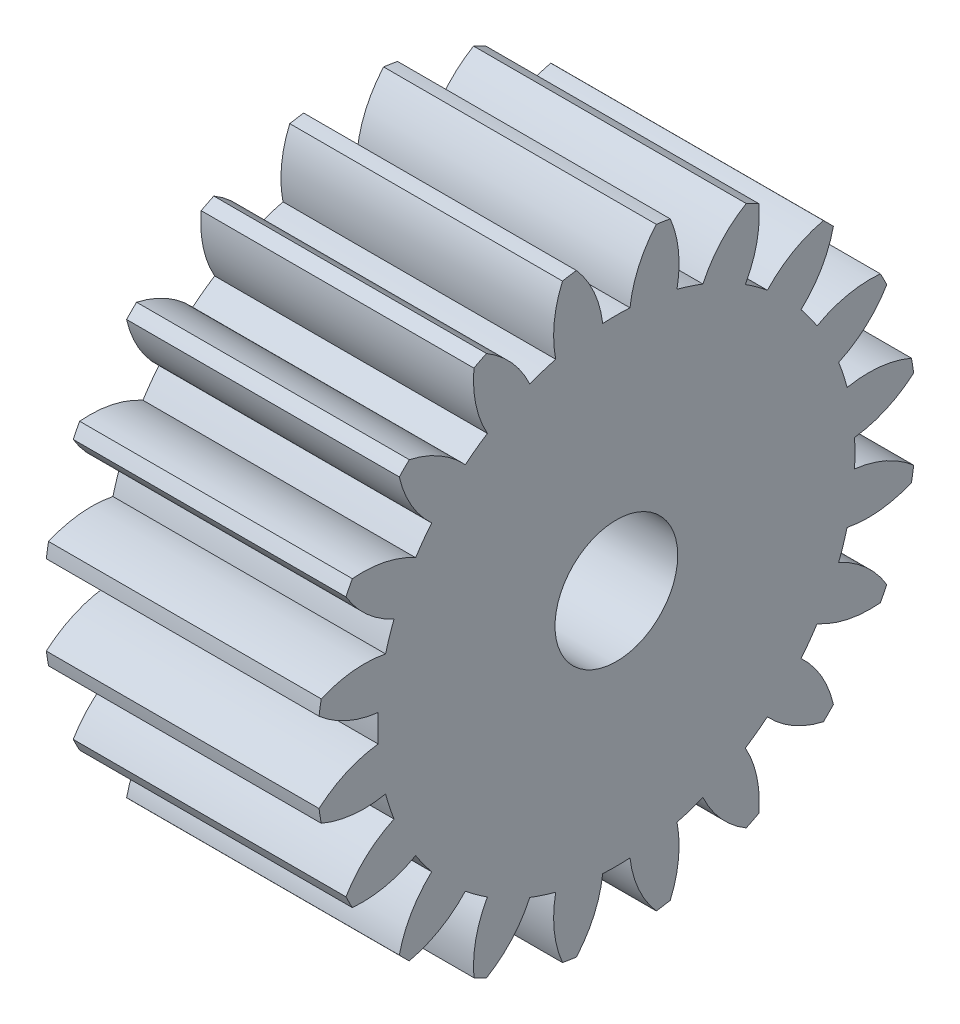
SolidWorks part; units mm, degrees
ref_plane "Plane1" through (0, 0, 0) normal (0, 0, 1) x (1, 0, 0)
ref_plane "Plane2" through (0, 0, 0) normal (0, 1, 0) x (1, 0, 0)
ref_plane "Plane3" through (0, 0, 0) normal (1, 0, 0) x (0, 0, -1)
other "Configuration Table"
sketch "HoldingSke" plane through (0, 0, 0) normal (0, 1, 0) x (1, 0, 0)
  line L0 (0, 0) -> (0.9397, -0.342)
  line L1 (-15, 0) -> (100, 0) construction
  line L2 (0, 0) -> (-2.1039, 2.3779)
  line L3 (0, 0) -> (-11.863, 4.5341)
  line L4 (0, 0) -> (8.1152, 2.9537)
  line L5 (0, 0) -> (-46.8476, -17.4728)
  line L6 (0, 0) -> (-8.2896, -5.593)
  line L7 (-2.1039, 2.3779) -> (8.6586, 51.2059)
  line L8 (-76.2, 54.61) -> (-75.5, 54.61)
  line L9 (-71.009, 38.7566) -> (-53.1078, 45.2721)
  line L10 (-76.2, 71.12) -> (104.1128, 71.12)
  line L11 (0, 0) -> (-10, 0)
  line L12 (-76.2, 101.6) -> (-76.162, 101.6)
  line L13 (24.9733, 27.94) -> (52.9518, 28.4284)
  line L14 (24.9733, 27.94) -> (24.9743, 27.94)
  line L15 (24.9733, 27.94) -> (100.4006, 29.5858)
  line L16 (-63.627, -1) -> (-12.827, -1)
  circle A0 centre (0, 0) radius 2
  circle A1 centre (0, 0) radius 8.749
  circle A2 centre (0, 0) radius 37.5
  circle A3 centre (0, 0) radius 2
  dimension "MHD" = 17.498
  dimension "Hub_dia" = 75
  dimension "Bore" = 4
  dimension "MBD" = 4
  dimension "Num_teeth" = 20
  dimension "Pitch" = 1
  dimension "Overall_len" = 50
  dimension "Show_teeth" = 20
  dimension "Thickness" = 10
  dimension "OAL" = 50.0001
  dimension "T_dim" = 0.7
  dimension "Ap" = 20
  dimension "H" = 19.05
  dimension "Pitch_radius" = 180.3128
  dimension "Width" = 10
  dimension "Backlash" = 0.038
  dimension "Addendum_fac" = 1
  dimension "Dedendum_fac" = 1.25
  dimension "Clearance_fac" = 0.25
  dimension "Dedendum_add" = 0.001
  dimension "Module" = 1
sketch "BasProSke" plane through (0, 0, 0) normal (0, 1, 0) x (1, 0, 0)
  line L0 (-10, 0) -> (60, 0) construction
  line L1 (0, 0) -> (0, 11)
  line L2 (0, 0) -> (10, 0)
  line L3 (10, 0) -> (10, 11)
  line L4 (10, 11) -> (0, 11)
  dimension "Thickness" = 10
  dimension "Diameter" = 22
revolve "Base-Revolve" add sketch "BasProSke" angle 360 about L0
sketch "TooCutSke" plane through (0, 0, 0) normal (1, 0, 0) x (0, 0, -1)
  line L1 (0, 0) -> (0, 107) construction
  line L2 (0, 0) -> (-0.8511, 9.9637) construction
  line L3 (0, 0) -> (-3.1206, 19.7028) construction
  line L4 (-0.8511, 9.9637) -> (-1.5603, 9.8514) construction
  arc A0 (0.4999, 8.7347) -> (-0.4999, 8.7347) centre (0, 0) ccw
  arc A1 (1.4852, 10.9249) -> (-1.4852, 10.9249) centre (0, 0) ccw
  circle A2 centre (0, 0) radius 10 construction
  circle A3 centre (0, 0) radius 9.3969 construction
  arc A4 (-0.4999, 8.7347) -> (-1.4852, 10.9249) centre (-4.4722, 8.2645) ccw
  arc A5 (1.4852, 10.9249) -> (0.4999, 8.7347) centre (4.4722, 8.2645) ccw
  dimension "Root_dia" = 17.498
  dimension "Overcut_dia" = 22.0508
  dimension "Pitch_dia" = 20
  dimension "Base_dia" = 18.7939
  dimension "Flank_rad" = 4
  dimension "Half_ang" = 9
  dimension "Half_CT" = 0.7181
extrude "ToothCut" cut sketch "TooCutSke" along normal through all
fillet "Breaks" [suppressed] radius 0.02
fillet "RootFillets" [suppressed] radius 0.251
pattern_circular "TeethCuts" count 20 every 18 about axis through (-10, 0, 0) along (1, 0, 0) of "ToothCut", "RootFillets", "Breaks"
sketch "HubNeaOneSke" plane through (0, 0, 0) normal (-1, 0, 0) x (0, 0, 1)
  circle A0 centre (0, 0) radius 8.749
  dimension "Diameter" = 17.498
extrude "HubNearOne" [suppressed] add sketch "HubNeaOneSke" along normal blind 40.0001
sketch "HubNeaBotSke" plane through (0, 0, 0) normal (-1, 0, 0) x (0, 0, 1)
  circle A0 centre (0, 0) radius 8.749
  dimension "Diameter" = 17.498
extrude "HubNearBoth" [suppressed] add sketch "HubNeaBotSke" along normal blind 20
ref_plane "FarPln" through (10, 0, 0) normal (1, 0, 0) x (0, 0, -1)
sketch "HubFarSke" plane through (10, 0, 0) normal (1, 0, 0) x (0, 0, -1)
  circle A0 centre (0, 0) radius 8.749
  dimension "Diameter" = 17.498
extrude "HubFar" [suppressed] add sketch "HubFarSke" along normal blind 20
sketch "BorSke" plane through (0, 0, 0) normal (1, 0, 0) x (0, 0, -1)
  circle A0 centre (0, 0) radius 2
  dimension "Diameter" = 4
extrude "Bore" cut sketch "BorSke" along normal mid plane 100.0001
sketch "KeySke" plane through (0, 0, 0) normal (1, 0, 0) x (0, 0, -1)
  line L0 (-0.8, 0) -> (-0.8, 2.7)
  line L1 (-0.8, 2.7) -> (0.8, 2.7)
  line L2 (0.8, 2.7) -> (0.8, 0)
  line L3 (0, 0) -> (0, 34) construction
  line L4 (-0.8, 0) -> (0.8, 0)
  dimension "Offset" = 2.7
  dimension "Width" = 1.6
extrude "Keyway" [suppressed] cut sketch "KeySke" along normal mid plane 100.0001
pattern_circular "Keyway2" [suppressed] count 2 every 90 about axis through (-10, 0, 0) along (1, 0, 0)
sketch "Sketch1" plane through (10, 0, 0) normal (1, 0, 0) x (0, 0, -1)
  circle A0 centre (0, 0) radius 2.25
extrude "Cut-Extrude1" cut sketch "Sketch1" against normal through all
equation "' \"Module@HoldingSke\" = 6.35"
equation "' \"Num_teeth@HoldingSke\" = 12"
equation "' \"Ap@HoldingSke\" =  20"
equation "' \"Ap@HoldingSke\" = 20"
equation "' \"Width@HoldingSke\" = 0.5 * 25.4"
equation "' \"Hub_dia@HoldingSke\"= 1 * 25.4"
equation "' \"Hub_dia@HoldingSke\" = 1 * 25.4"
equation "' \"Overall_len@HoldingSke\" = 1.0 * 25.4"
equation "' \"Bore@HoldingSke\" = 0.75 * 25.4"
equation "' \"T_dim@HoldingSke\" = 0.1 * 25.4"
equation "' \"Width@KeySke\" = 0.25 * 25.4"
equation "' \"Show_teeth@HoldingSke\" = 13"
equation "' \"Backlash@HoldingSke\" = 0.009 * 25.4"
equation "' \"Addendum_fac@HoldingSke\" = 1.0"
equation "' \"Dedendum_fac@HoldingSke\" = 1.25"
equation "' \"Dedendum_add@HoldingSke\" = 0.00005 * 25.4"
equation "' \"Clearance_fac@HoldingSke\" = 0.25"
equation "\"Pitch@HoldingSke\" = 1 / \"Module@HoldingSke\""
equation "\"Overcut_dia@TooCutSke\" = (\"Num_teeth@HoldingSke\" + 2 * \"Addendum_fac@HoldingSke\") / \"Pitch@HoldingSke\" + 0.002 * 25.4"
equation "\"Pitch_dia@TooCutSke\" = \"Num_teeth@HoldingSke\" / \"Pitch@HoldingSke\""
equation "\"Base_dia@TooCutSke\" = \"Num_teeth@HoldingSke\" / \"Pitch@HoldingSke\" * cos((\"Ap@HoldingSke\"  * 3.14159265 / 180))"
equation "\"Root_dia@TooCutSke\" = (\"Num_teeth@HoldingSke\" + 2) / \"Pitch@HoldingSke\" - 2 * (\"Addendum_fac@HoldingSke\" + \"Dedendum_fac@HoldingSke\") / \"Pitch@HoldingSke\" - \"Dedendum_add@HoldingSke\" * 2"
equation "\"Half_ang@TooCutSke\" = 180 / \"Num_teeth@HoldingSke\""
equation "\"Half_CT@TooCutSke\" = \"Num_teeth@HoldingSke\" / \"Pitch@HoldingSke\" * sin((3.14159265 / 2 / \"Num_teeth@HoldingSke\")) / 2 - 7 * \"Backlash@HoldingSke\" / 4"
equation "\"Flank_rad@TooCutSke\" = \"Num_teeth@HoldingSke\" / \"Pitch@HoldingSke\" / 5"
equation "\"Radius@RootFillets\" = \"Clearance_fac@HoldingSke\" / \"Pitch@HoldingSke\" + \"Dedendum_add@HoldingSke\""
equation "\"Break_rad@Breaks\" = 0.02 / \"Pitch@HoldingSke\""
equation "\"Thickness@HoldingSke\" = \"Width@HoldingSke\""
equation "\"OAL@HoldingSke\" = \"Thickness@HoldingSke\""
equation "\"MHD@HoldingSke\" = (\"Num_teeth@HoldingSke\" + 2) / \"Pitch@HoldingSke\" - 2 * (\"Addendum_fac@HoldingSke\" + \"Dedendum_fac@HoldingSke\")  / \"Pitch@HoldingSke\" - \"Dedendum_add@HoldingSke\" * 2"
equation "\"MBD@HoldingSke\" = (\"Num_teeth@HoldingSke\" + 2) / \"Pitch@HoldingSke\" - 2 * (\"Addendum_fac@HoldingSke\" + \"Dedendum_fac@HoldingSke\")  / \"Pitch@HoldingSke\" - \"Dedendum_add@HoldingSke\" * 2 - 0.002 * 25.4"
equation "\"MHD@HoldingSke\" = ((sgn( \"MHD@HoldingSke\" - \"Hub_dia@HoldingSke\" )-1)*( \"MHD@HoldingSke\" - \"Hub_dia@HoldingSke\" ))/-2+ \"Hub_dia@HoldingSke\""
equation "\"MBD@HoldingSke\" = ((sgn( \"MBD@HoldingSke\" - \"Bore@HoldingSke\" )-1)*( \"MBD@HoldingSke\" - \"Bore@HoldingSke\" ))/-2+ \"Bore@HoldingSke\""
equation "\"OAL@HoldingSke\" = ((sgn( \"OAL@HoldingSke\" - \"Overall_len@HoldingSke\" )+1)*( \"OAL@HoldingSke\" - \"Overall_len@HoldingSke\" ))/2 + \"Overall_len@HoldingSke\" + 0.000002 * 25.4"
equation "\"Num_teeth@TeethCuts\" = int( \"Show_teeth@HoldingSke\" ) + 1"
equation "\"Num_teeth@TeethCuts\" = ((sgn( \"Num_teeth@TeethCuts\" - \"Num_teeth@HoldingSke\" )-1)*( \"Num_teeth@TeethCuts\" - \"Num_teeth@HoldingSke\" ))/-2+ \"Num_teeth@HoldingSke\""
equation "\"Num_teeth@TeethCuts\" = ((sgn( \"Num_teeth@TeethCuts\" - 2.0)+1)*( \"Num_teeth@TeethCuts\" - 2.0))/2 +2.0"
equation "\"Angle@TeethCuts\" = 360.0 / \"Num_teeth@HoldingSke\""
equation "\"Diameter@BasProSke\" = (\"Num_teeth@HoldingSke\" + 2 * \"Addendum_fac@HoldingSke\") / \"Pitch@HoldingSke\""
equation "\"Thickness@BasProSke\"  = \"Thickness@HoldingSke\""
equation "' \"Fillet_rad@BasProSke\" =  \"Thickness@HoldingSke\" * 0.05"
equation "' \"Fillet_rad@BasProSke\" = \"Thickness@HoldingSke\" * 0.05"
equation "\"MHD@HoldingSke\" = ((sgn( \"MHD@HoldingSke\" - \"Root_dia@TooCutSke\" )-1)*( \"MHD@HoldingSke\" - \"Root_dia@TooCutSke\" ))/-2+ \"Root_dia@TooCutSke\""
equation "\"Diameter@HubNeaOneSke\" = \"MHD@HoldingSke\""
equation "\"Length@HubNearOne\" = \"OAL@HoldingSke\" - \"Thickness@BasProSke\""
equation "\"Diameter@HubNeaBotSke\" = \"MHD@HoldingSke\""
equation "\"Length@HubNearBoth\" = ( \"OAL@HoldingSke\" - \"Thickness@BasProSke\" ) / 2.0"
equation "\"Thickness@FarPln\" = \"Thickness@BasProSke\""
equation "\"Diameter@HubFarSke\" = \"MHD@HoldingSke\""
equation "\"Length@HubFar\" = ( \"OAL@HoldingSke\" - \"Thickness@BasProSke\" ) / 2.0"
equation "\"Diameter@BorSke\" = \"MBD@HoldingSke\""
equation "\"D1@Bore\" = \"OAL@HoldingSke\" * 2.0"
equation "\"D1@Keyway\" = \"OAL@HoldingSke\" * 2.0"
equation "\"Offset@KeySke\" = \"T_dim@HoldingSke\" + \"MBD@HoldingSke\" / 2.0"
